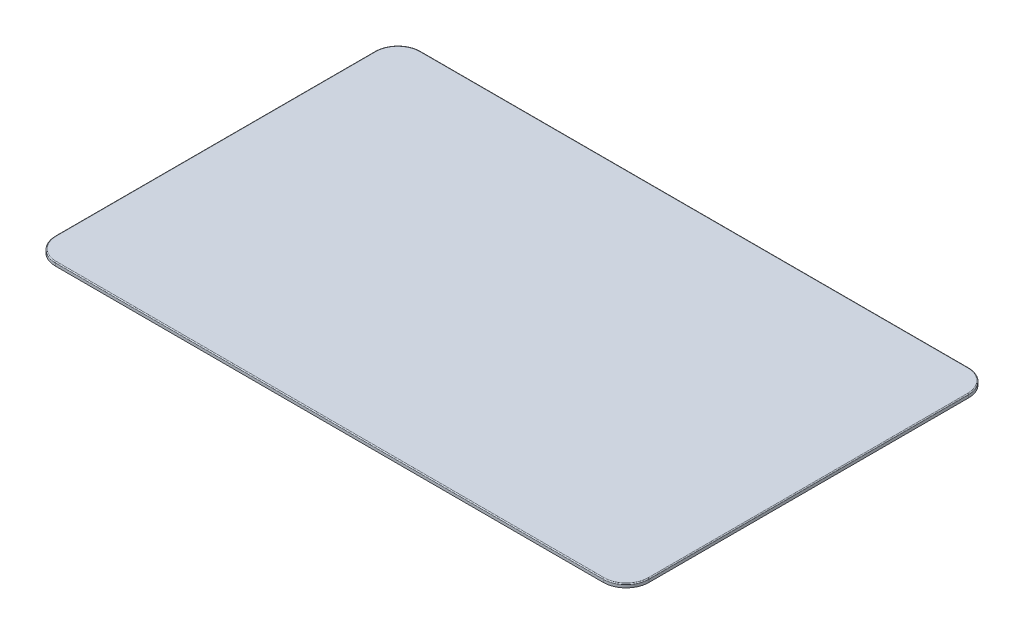
SolidWorks part; units mm, degrees
ref_plane "Спереди" through (0, 0, 0) normal (0, 0, 1) x (1, 0, 0)
ref_plane "Сверху" through (0, 0, 0) normal (0, 1, 0) x (1, 0, 0)
ref_plane "Справа" through (0, 0, 0) normal (1, 0, 0) x (0, 0, -1)
sketch "Эскиз1" plane through (0, 0, 0) normal (0, 1, 0) x (1, 0, 0)
  line L1 (-600, -400) -> (600, -400)
  line L2 (-650, -350) -> (-650, 350)
  line L3 (-600, 400) -> (600, 400)
  line L4 (650, -350) -> (650, 350)
  line L5 (-650, -400) -> (650, 400) construction
  line L6 (-650, 400) -> (650, -400) construction
  arc A0 (-600, 400) -> (-650, 350) centre (-600, 350) ccw
  arc A1 (600, 400) -> (650, 350) centre (600, 350) cw
  arc A2 (650, -350) -> (600, -400) centre (600, -350) cw
  arc A3 (-600, -400) -> (-650, -350) centre (-600, -350) cw
  point P0 (0, 0)
  dimension "D1" = 50
  dimension "D4" = 50
  dimension "D2" = 1300
  dimension "D3" = 800
extrude "Бобышка-Вытянуть1" add sketch "Эскиз1" along normal blind 8
fillet "Скругление1" radius 2 8 edges at (-635.3553, 8, -385.3553) (0, 8, -400) (635.3553, 8, -385.3553) (650, 8, 0) (635.3553, 8, 385.3553) (0, 8, 400) (-635.3553, 8, 385.3553) (-650, 8, 0)
sketch "Эскиз2" plane through (0, 0, 0) normal (0, -1, 0) x (1, 0, 0)
  line L0 (0, 398) -> (0, 115.0711) construction
  line L1 (-498, -35) -> (-405.9312, -35) construction
  line L2 (-494.82, 35) -> (-402.7512, 35) construction
  line L3 (-498, -100.1909) -> (-498, 80.8489) construction
  line L4 (-505.5, -118.7139) -> (-423, -118.7139)
  line L5 (-480.5, -93.7139) -> (-448, -93.7139)
  line L6 (-418, 113.7139) -> (-418, 19.5)
  line L7 (250, 398) -> (250, -398) construction
  line L8 (-250, 398) -> (-250, -398) construction
  line L9 (-648, 0) -> (648, 0) construction
  line L10 (302.5206, -212.9276) -> (307.7592, -212.906)
  line L12 (259.7408, -280.6043) -> (259.7408, -218.094)
  line L13 (262.2408, -283.1043) -> (308.0492, -283.1043)
  line L14 (265.5, -179.2861) -> (207.5, -179.2861)
  line L15 (-505.5, 118.7139) -> (-423, 118.7139)
  line L16 (-443, 88.7139) -> (-443, -88.7139)
  line L17 (-480.5, 93.7139) -> (-448, 93.7139)
  line L18 (-485.5, 84.9278) -> (-485.5, 88.7139)
  line L19 (-510.5, 85.0723) -> (-510.5, 113.7139)
  line L20 (-523.5388, 12.3957) -> (-523.2695, 77.6043)
  line L21 (418, -14.5) -> (302.5, -14.5)
  line L22 (418, 14.5) -> (302.5, 14.5)
  line L23 (418, -14.5) -> (418, -113.7139)
  line L24 (265.5, 174.2861) -> (207.5, 174.2861)
  line L25 (-515.5206, -80.0724) -> (-520.7592, -80.094)
  line L26 (267.5, 199.2861) -> (232.5, 199.2861)
  line L27 (270.5, -174.2861) -> (270.5, 169.2861)
  line L28 (197.4794, 212.9276) -> (192.2408, 212.906)
  line L29 (240.2592, 280.6043) -> (240.2592, 215.6043)
  line L30 (272.5, 208.0722) -> (272.5, 204.2861)
  line L31 (237.7592, 283.1043) -> (191.9508, 283.1043)
  line L32 (237.7592, 213.094) -> (232.4794, 213.0722)
  line L33 (310.5388, -280.6043) -> (310.2695, -215.3957)
  line L34 (-472.7408, -12.3957) -> (-472.7408, -77.3957)
  line L35 (297.5, -207.9277) -> (297.5, -19.5)
  line L36 (202.5, -207.9277) -> (202.5, -184.2861)
  line L37 (-475.2408, 79.906) -> (-480.5206, 79.9278)
  line L38 (-302.5206, 212.9276) -> (-307.7592, 212.906)
  line L39 (-265.5, 179.2861) -> (-207.5, 179.2861)
  line L40 (-259.7408, 280.6043) -> (-259.7408, 218.1043)
  line L41 (189.4612, -280.6043) -> (189.7305, -215.3957)
  line L42 (-262.2408, 283.1043) -> (-308.0492, 283.1043)
  line L43 (-254.7408, 213.1043) -> (-245.2592, 213.1043)
  line L44 (237.7592, -283.1043) -> (191.9508, -283.1043)
  line L46 (240.2592, -280.6043) -> (240.2592, -218.094)
  line L47 (197.4794, -212.9276) -> (192.2408, -212.906)
  line L50 (-310.5388, 280.6043) -> (-310.2695, 215.3957)
  line L51 (-297.5, 207.9277) -> (-297.5, 14.5)
  line L52 (-202.5, 207.9277) -> (-202.5, 184.2861)
  line L53 (-189.4612, 280.6043) -> (-189.7305, 215.3957)
  line L54 (-265.5, -174.2861) -> (-207.5, -174.2861)
  line L55 (-267.5, -199.2861) -> (-232.5, -199.2861)
  line L56 (-475.2408, -9.8957) -> (-521.0492, -9.8957)
  line L57 (-475.2408, -79.906) -> (-480.5206, -79.9278)
  line L58 (-475.2408, 9.8957) -> (-521.0492, 9.8957)
  line L59 (-523.5388, -12.3957) -> (-523.2695, -77.6043)
  line L60 (-510.5, -85.0723) -> (-510.5, -113.7139)
  line L61 (-472.7408, 12.3957) -> (-472.7408, 77.3957)
  line L62 (-515.5206, 80.0724) -> (-520.7592, 80.094)
  line L63 (-485.5, -84.9278) -> (-485.5, -88.7139)
  line L65 (-197.4794, -212.9276) -> (-192.2408, -212.906)
  line L66 (-240.2592, -280.6043) -> (-240.2592, -215.6043)
  line L67 (-272.5, -208.0722) -> (-272.5, -204.2861)
  line L68 (-237.7592, -283.1043) -> (-191.9508, -283.1043)
  line L69 (-237.7592, -213.094) -> (-232.4794, -213.0722)
  line L70 (485.5, -84.9278) -> (485.5, -88.7139)
  line L71 (-189.4612, -280.6043) -> (-189.7305, -215.3957)
  line L72 (-202.5, -207.9277) -> (-202.5, -179.2861)
  line L73 (-297.5, -207.9277) -> (-297.5, -14.5)
  line L74 (515.5206, 80.0724) -> (520.7592, 80.094)
  line L75 (472.7408, 12.3957) -> (472.7408, 77.3957)
  line L76 (510.5, -85.0723) -> (510.5, -113.7139)
  line L77 (523.5388, -12.3957) -> (523.2695, -77.6043)
  line L78 (475.2408, 9.8957) -> (521.0492, 9.8957)
  line L79 (475.2408, -79.906) -> (480.5206, -79.9278)
  line L80 (475.2408, -9.8957) -> (521.0492, -9.8957)
  line L81 (-102.1767, 35.0711) -> (-96.9381, 35.0927)
  line L82 (-142.4565, 34.9047) -> (-137.1767, 34.9265)
  line L83 (-94.1585, -32.6057) -> (-94.4278, 32.603)
  line L84 (-144.9565, -32.6056) -> (-144.9565, 32.3944)
  line L85 (-142.4565, -35.1056) -> (-96.6482, -35.1056)
  line L86 (-42.1767, 35.0711) -> (-36.9381, 35.0927)
  line L87 (-82.4565, 34.9047) -> (-77.1767, 34.9265)
  line L88 (-34.1585, -32.6057) -> (-34.4278, 32.603)
  line L89 (-84.9565, -32.6056) -> (-84.9565, 32.3944)
  line L90 (-82.4565, -35.1056) -> (-36.6482, -35.1056)
  line L91 (17.8233, 35.0711) -> (23.0619, 35.0927)
  line L92 (-22.4565, 34.9047) -> (-17.1767, 34.9265)
  line L93 (25.8415, -32.6057) -> (25.5722, 32.603)
  line L94 (-24.9565, -32.6056) -> (-24.9565, 32.3944)
  line L95 (-22.4565, -35.1056) -> (23.3518, -35.1056)
  line L96 (77.8233, 35.0711) -> (83.0619, 35.0927)
  line L97 (37.5435, 34.9047) -> (42.8233, 34.9265)
  line L98 (85.8415, -32.6057) -> (85.5722, 32.603)
  line L99 (35.0435, -32.6056) -> (35.0435, 32.3944)
  line L100 (37.5435, -35.1056) -> (83.3518, -35.1056)
  line L101 (137.9695, 35.0717) -> (143.0619, 35.0927)
  line L102 (97.5435, 34.9047) -> (102.0709, 34.9234)
  line L103 (145.8415, -32.6057) -> (145.5722, 32.603)
  line L104 (95.0435, -32.6056) -> (95.0435, 32.3944)
  line L105 (97.5435, -35.1056) -> (143.3518, -35.1056)
  line L106 (-132.1973, 39.9265) -> (-132.1973, 110.0711)
  line L107 (-107.1973, 40.071) -> (-107.1973, 85.0711)
  line L108 (0, 0) -> (0, -400) construction
  line L109 (67.8027, 80.0711) -> (17.8027, 80.0711)
  line L110 (107.1973, 40.071) -> (107.1973, 85.0711)
  line L112 (-310.5388, -280.6043) -> (-310.2695, -215.3957)
  line L114 (-237.7592, 283.1043) -> (-191.9508, 283.1043)
  line L116 (-240.2592, 280.6043) -> (-240.2592, 218.1043)
  line L117 (-197.4794, 212.9276) -> (-192.2408, 212.906)
  line L118 (-270.5, 174.2861) -> (-270.5, -169.2861)
  line L122 (-418, -19.5) -> (-418, -113.7139)
  line L123 (189.4612, 280.6043) -> (189.7305, 215.3957)
  line L124 (202.5, 207.9277) -> (202.5, 179.2861)
  line L125 (297.5, 207.9277) -> (297.5, 19.5)
  line L126 (310.5388, 280.6043) -> (310.2695, 215.3957)
  line L127 (262.2408, 213.094) -> (267.5206, 213.0722)
  line L128 (262.2408, 283.1043) -> (308.0492, 283.1043)
  line L129 (259.7408, 280.6043) -> (259.7408, 215.6043)
  line L130 (227.5, 208.0722) -> (227.5, 204.2861)
  line L131 (302.5206, 212.9276) -> (307.7592, 212.906)
  line L132 (498, -100.1909) -> (498, 80.8489) construction
  line L133 (475.2408, 79.906) -> (480.5206, 79.9278)
  line L134 (472.7408, -12.3957) -> (472.7408, -77.3957)
  line L135 (515.5206, -80.0724) -> (520.7592, -80.094)
  line L136 (523.5388, 12.3957) -> (523.2695, 77.6043)
  line L137 (-413, 14.5) -> (-297.5, 14.5)
  line L138 (-413, -14.5) -> (-297.5, -14.5)
  line L139 (-262.2408, -213.094) -> (-267.5206, -213.0722)
  line L140 (510.5, 85.0723) -> (510.5, 113.7139)
  line L141 (485.5, 84.9278) -> (485.5, 88.7139)
  line L142 (-262.2408, -283.1043) -> (-308.0492, -283.1043)
  line L143 (494.82, 35) -> (402.7512, 35) construction
  line L144 (498, -35) -> (405.9312, -35) construction
  line L145 (480.5, 93.7139) -> (448, 93.7139)
  line L146 (443, 88.7139) -> (443, -88.7139)
  line L147 (505.5, 118.7139) -> (423, 118.7139)
  line L148 (418, 113.7139) -> (418, 14.5)
  line L149 (480.5, -93.7139) -> (448, -93.7139)
  line L150 (-259.7408, -280.6043) -> (-259.7408, -215.6043)
  line L151 (505.5, -118.7139) -> (423, -118.7139)
  line L152 (-227.5, -208.0722) -> (-227.5, -204.2861)
  line L153 (-302.5206, -212.9276) -> (-307.7592, -212.906)
  line L154 (72.8027, 40.071) -> (72.8027, 50.0711)
  line L155 (47.8027, 39.9265) -> (47.8027, 50.0711)
  line L156 (12.8027, 40.071) -> (12.8027, 50.0711)
  line L157 (-12.1973, 39.9265) -> (-12.1973, 50.0711)
  line L158 (-47.1973, 40.071) -> (-47.1973, 50.0711)
  line L159 (-72.1973, 39.9265) -> (-72.1973, 50.0711)
  line L160 (254.7408, -213.094) -> (245.2592, -213.094)
  line L161 (42.8027, 55.0711) -> (17.8027, 55.0711)
  line L162 (-17.1973, 55.0711) -> (-42.1973, 55.0711)
  line L163 (102.1973, 90.0711) -> (17.1973, 90.0711)
  line L164 (72.8027, 50.0711) -> (72.8027, 75.0711)
  line L165 (-72.1973, 50.0711) -> (-72.1973, 75.0711)
  line L166 (127.8027, 115.0711) -> (-127.1973, 115.0711)
  line L167 (-102.1973, 90.0711) -> (-17.1973, 90.0711)
  line L170 (-17.1973, 80.0711) -> (-67.1973, 80.0711)
  line L171 (132.8027, 40.071) -> (132.8027, 110.0711)
  arc A0 (240.2592, -218.094) -> (245.2592, -213.094) centre (245.2592, -218.094) cw
  arc A1 (297.5, -207.9277) -> (302.5206, -212.9276) centre (302.5, -207.9277) ccw
  arc A2 (310.2695, -215.3957) -> (307.7592, -212.906) centre (310.2592, -212.8957) ccw
  arc A3 (267.5, 199.2861) -> (272.5, 204.2861) centre (267.5, 204.2861) ccw
  arc A4 (227.5, 204.2861) -> (232.5, 199.2861) centre (232.5, 204.2861) ccw
  arc A5 (202.5, -184.2861) -> (207.5, -179.2861) centre (207.5, -184.2861) cw
  arc A6 (308.0492, -283.1043) -> (310.5388, -280.6043) centre (310.5492, -283.1043) ccw
  arc A7 (259.7408, -280.6043) -> (262.2408, -283.1043) centre (259.7408, -283.1043) ccw
  arc A8 (240.2592, -280.6043) -> (237.7592, -283.1043) centre (240.2592, -283.1043) cw
  arc A9 (191.9508, -283.1043) -> (189.4612, -280.6043) centre (189.4508, -283.1043) cw
  arc A10 (270.5, 169.2861) -> (265.5, 174.2861) centre (265.5, 169.2861) ccw
  arc A11 (510.5, 113.7139) -> (505.5, 118.7139) centre (505.5, 113.7139) ccw
  arc A12 (265.5, -179.2861) -> (270.5, -174.2861) centre (265.5, -174.2861) ccw
  arc A13 (189.7305, -215.3957) -> (192.2408, -212.906) centre (189.7408, -212.8957) cw
  arc A14 (202.5, -207.9277) -> (197.4794, -212.9276) centre (197.5, -207.9277) cw
  arc A15 (254.7408, -213.094) -> (259.7408, -218.094) centre (254.7408, -218.094) cw
  arc A16 (-240.2592, 218.1043) -> (-245.2592, 213.1043) centre (-245.2592, 218.1043) cw
  arc A17 (505.5, -118.7139) -> (510.5, -113.7139) centre (505.5, -113.7139) ccw
  arc A18 (-254.7408, 213.1043) -> (-259.7408, 218.1043) centre (-254.7408, 218.1043) cw
  arc A19 (-202.5, 184.2861) -> (-207.5, 179.2861) centre (-207.5, 184.2861) cw
  arc A20 (232.4794, 213.0722) -> (227.5, 208.0722) centre (232.5, 208.0722) ccw
  arc A21 (202.5, 207.9277) -> (197.4794, 212.9276) centre (197.5, 207.9277) ccw
  arc A22 (189.7305, 215.3957) -> (192.2408, 212.906) centre (189.7408, 212.8957) ccw
  arc A23 (237.7592, 213.094) -> (240.2592, 215.6043) centre (240.2592, 213.1043) ccw
  arc A24 (191.9508, 283.1043) -> (189.4612, 280.6043) centre (189.4508, 283.1043) ccw
  arc A25 (240.2592, 280.6043) -> (237.7592, 283.1043) centre (240.2592, 283.1043) ccw
  arc A26 (259.7408, 280.6043) -> (262.2408, 283.1043) centre (259.7408, 283.1043) cw
  arc A27 (308.0492, 283.1043) -> (310.5388, 280.6043) centre (310.5492, 283.1043) cw
  arc A28 (262.2408, 213.094) -> (259.7408, 215.6043) centre (259.7408, 213.1043) cw
  arc A29 (310.2695, 215.3957) -> (307.7592, 212.906) centre (310.2592, 212.8957) cw
  arc A30 (297.5, 207.9277) -> (302.5206, 212.9276) centre (302.5, 207.9277) cw
  arc A31 (267.5206, 213.0722) -> (272.5, 208.0722) centre (267.5, 208.0722) cw
  arc A32 (202.5, 179.2861) -> (207.5, 174.2861) centre (207.5, 179.2861) ccw
  arc A33 (-270.5, -169.2861) -> (-265.5, -174.2861) centre (-265.5, -169.2861) ccw
  arc A34 (485.5, 88.7139) -> (480.5, 93.7139) centre (480.5, 88.7139) ccw
  arc A35 (-443, -88.7139) -> (-448, -93.7139) centre (-448, -88.7139) cw
  arc A36 (480.5206, 79.9278) -> (485.5, 84.9278) centre (480.5, 84.9278) ccw
  arc A37 (510.5, 85.0723) -> (515.5206, 80.0724) centre (515.5, 85.0723) ccw
  arc A38 (472.7408, -12.3957) -> (475.2408, -9.8957) centre (472.7408, -9.8957) cw
  arc A39 (521.0492, -9.8957) -> (523.5388, -12.3957) centre (523.5492, -9.8957) cw
  arc A40 (475.2408, -79.906) -> (472.7408, -77.3957) centre (472.7408, -79.8957) cw
  arc A41 (523.2695, -77.6043) -> (520.7592, -80.094) centre (523.2592, -80.1043) cw
  arc A42 (510.5, -85.0723) -> (515.5206, -80.0724) centre (515.5, -85.0723) cw
  arc A43 (480.5206, -79.9278) -> (485.5, -84.9278) centre (480.5, -84.9278) cw
  arc A44 (523.2695, 77.6043) -> (520.7592, 80.094) centre (523.2592, 80.1043) ccw
  arc A45 (-418, -113.7139) -> (-423, -118.7139) centre (-423, -113.7139) cw
  arc A46 (485.5, -88.7139) -> (480.5, -93.7139) centre (480.5, -88.7139) cw
  arc A47 (475.2408, 79.906) -> (472.7408, 77.3957) centre (472.7408, 79.8957) ccw
  arc A48 (521.0492, 9.8957) -> (523.5388, 12.3957) centre (523.5492, 9.8957) ccw
  arc A49 (472.7408, 12.3957) -> (475.2408, 9.8957) centre (472.7408, 9.8957) ccw
  arc A50 (-443, 88.7139) -> (-448, 93.7139) centre (-448, 88.7139) ccw
  arc A51 (-418, 113.7139) -> (-423, 118.7139) centre (-423, 113.7139) ccw
  arc A52 (418, 113.7139) -> (423, 118.7139) centre (423, 113.7139) cw
  arc A53 (443, 88.7139) -> (448, 93.7139) centre (448, 88.7139) cw
  arc A54 (418, -113.7139) -> (423, -118.7139) centre (423, -113.7139) ccw
  arc A55 (443, -88.7139) -> (448, -93.7139) centre (448, -88.7139) ccw
  arc A56 (-472.7408, 12.3957) -> (-475.2408, 9.8957) centre (-472.7408, 9.8957) cw
  arc A57 (-521.0492, 9.8957) -> (-523.5388, 12.3957) centre (-523.5492, 9.8957) cw
  arc A58 (-475.2408, 79.906) -> (-472.7408, 77.3957) centre (-472.7408, 79.8957) cw
  arc A59 (-485.5, -88.7139) -> (-480.5, -93.7139) centre (-480.5, -88.7139) ccw
  arc A60 (-523.2695, 77.6043) -> (-520.7592, 80.094) centre (-523.2592, 80.1043) cw
  arc A61 (-480.5206, -79.9278) -> (-485.5, -84.9278) centre (-480.5, -84.9278) ccw
  arc A62 (-510.5, -85.0723) -> (-515.5206, -80.0724) centre (-515.5, -85.0723) ccw
  arc A63 (-523.2695, -77.6043) -> (-520.7592, -80.094) centre (-523.2592, -80.1043) ccw
  arc A64 (-475.2408, -79.906) -> (-472.7408, -77.3957) centre (-472.7408, -79.8957) ccw
  arc A65 (-521.0492, -9.8957) -> (-523.5388, -12.3957) centre (-523.5492, -9.8957) ccw
  arc A66 (-472.7408, -12.3957) -> (-475.2408, -9.8957) centre (-472.7408, -9.8957) ccw
  arc A67 (-510.5, 85.0723) -> (-515.5206, 80.0724) centre (-515.5, 85.0723) cw
  arc A68 (-480.5206, 79.9278) -> (-485.5, 84.9278) centre (-480.5, 84.9278) cw
  arc A69 (-485.5, 88.7139) -> (-480.5, 93.7139) centre (-480.5, 88.7139) cw
  arc A70 (-202.5, -179.2861) -> (-207.5, -174.2861) centre (-207.5, -179.2861) ccw
  arc A71 (-270.5, 174.2861) -> (-265.5, 179.2861) centre (-265.5, 174.2861) cw
  arc A72 (297.5, 19.5) -> (302.5, 14.5) centre (302.5, 19.5) ccw
  arc A73 (-297.5, 207.9277) -> (-302.5206, 212.9276) centre (-302.5, 207.9277) ccw
  arc A74 (-310.2695, 215.3957) -> (-307.7592, 212.906) centre (-310.2592, 212.8957) ccw
  arc A75 (297.5, -19.5) -> (302.5, -14.5) centre (302.5, -19.5) cw
  arc A76 (-308.0492, 283.1043) -> (-310.5388, 280.6043) centre (-310.5492, 283.1043) ccw
  arc A77 (-259.7408, 280.6043) -> (-262.2408, 283.1043) centre (-259.7408, 283.1043) ccw
  arc A78 (-240.2592, 280.6043) -> (-237.7592, 283.1043) centre (-240.2592, 283.1043) cw
  arc A79 (-191.9508, 283.1043) -> (-189.4612, 280.6043) centre (-189.4508, 283.1043) cw
  arc A80 (-418, 19.5) -> (-413, 14.5) centre (-413, 19.5) ccw
  arc A81 (-189.7305, 215.3957) -> (-192.2408, 212.906) centre (-189.7408, 212.8957) cw
  arc A82 (-202.5, 207.9277) -> (-197.4794, 212.9276) centre (-197.5, 207.9277) cw
  arc A83 (-418, -19.5) -> (-413, -14.5) centre (-413, -19.5) cw
  arc A84 (-267.5, -199.2861) -> (-272.5, -204.2861) centre (-267.5, -204.2861) ccw
  arc A85 (-227.5, -204.2861) -> (-232.5, -199.2861) centre (-232.5, -204.2861) ccw
  arc A86 (-505.5, -118.7139) -> (-510.5, -113.7139) centre (-505.5, -113.7139) cw
  arc A88 (-232.4794, -213.0722) -> (-227.5, -208.0722) centre (-232.5, -208.0722) ccw
  arc A89 (-202.5, -207.9277) -> (-197.4794, -212.9276) centre (-197.5, -207.9277) ccw
  arc A90 (-189.7305, -215.3957) -> (-192.2408, -212.906) centre (-189.7408, -212.8957) ccw
  arc A92 (-510.5, 113.7139) -> (-505.5, 118.7139) centre (-505.5, 113.7139) cw
  arc A93 (-237.7592, -213.094) -> (-240.2592, -215.6043) centre (-240.2592, -213.1043) ccw
  arc A94 (-191.9508, -283.1043) -> (-189.4612, -280.6043) centre (-189.4508, -283.1043) ccw
  arc A95 (-240.2592, -280.6043) -> (-237.7592, -283.1043) centre (-240.2592, -283.1043) ccw
  arc A96 (-259.7408, -280.6043) -> (-262.2408, -283.1043) centre (-259.7408, -283.1043) cw
  arc A97 (-308.0492, -283.1043) -> (-310.5388, -280.6043) centre (-310.5492, -283.1043) cw
  arc A98 (-262.2408, -213.094) -> (-259.7408, -215.6043) centre (-259.7408, -213.1043) cw
  arc A101 (-310.2695, -215.3957) -> (-307.7592, -212.906) centre (-310.2592, -212.8957) cw
  arc A102 (-297.5, -207.9277) -> (-302.5206, -212.9276) centre (-302.5, -207.9277) cw
  arc A103 (-267.5206, -213.0722) -> (-272.5, -208.0722) centre (-267.5, -208.0722) cw
  arc A104 (-137.1767, 34.9265) -> (-132.1973, 39.9265) centre (-137.1973, 39.9265) ccw
  arc A105 (-144.9565, -32.6056) -> (-142.4565, -35.1056) centre (-144.9565, -35.1056) ccw
  arc A106 (-107.1973, 40.071) -> (-102.1767, 35.0711) centre (-102.1973, 40.071) ccw
  arc A107 (-94.4278, 32.603) -> (-96.9381, 35.0927) centre (-94.4381, 35.103) ccw
  arc A108 (-142.4565, 34.9047) -> (-144.9565, 32.3944) centre (-144.9565, 34.8944) ccw
  arc A109 (-96.6482, -35.1056) -> (-94.1585, -32.6057) centre (-94.1482, -35.1056) ccw
  arc A110 (-77.1767, 34.9265) -> (-72.1973, 39.9265) centre (-77.1973, 39.9265) ccw
  arc A111 (-84.9565, -32.6056) -> (-82.4565, -35.1056) centre (-84.9565, -35.1056) ccw
  arc A112 (-47.1973, 40.071) -> (-42.1767, 35.0711) centre (-42.1973, 40.071) ccw
  arc A113 (-34.4278, 32.603) -> (-36.9381, 35.0927) centre (-34.4381, 35.103) ccw
  arc A114 (-82.4565, 34.9047) -> (-84.9565, 32.3944) centre (-84.9565, 34.8944) ccw
  arc A115 (-36.6482, -35.1056) -> (-34.1585, -32.6057) centre (-34.1482, -35.1056) ccw
  arc A116 (-17.1767, 34.9265) -> (-12.1973, 39.9265) centre (-17.1973, 39.9265) ccw
  arc A117 (-24.9565, -32.6056) -> (-22.4565, -35.1056) centre (-24.9565, -35.1056) ccw
  arc A118 (12.8027, 40.071) -> (17.8233, 35.0711) centre (17.8027, 40.071) ccw
  arc A119 (25.5722, 32.603) -> (23.0619, 35.0927) centre (25.5619, 35.103) ccw
  arc A120 (-22.4565, 34.9047) -> (-24.9565, 32.3944) centre (-24.9565, 34.8944) ccw
  arc A121 (23.3518, -35.1056) -> (25.8415, -32.6057) centre (25.8518, -35.1056) ccw
  arc A122 (42.8233, 34.9265) -> (47.8027, 39.9265) centre (42.8027, 39.9265) ccw
  arc A123 (35.0435, -32.6056) -> (37.5435, -35.1056) centre (35.0435, -35.1056) ccw
  arc A124 (72.8027, 40.071) -> (77.8233, 35.0711) centre (77.8027, 40.071) ccw
  arc A125 (85.5722, 32.603) -> (83.0619, 35.0927) centre (85.5619, 35.103) ccw
  arc A126 (37.5435, 34.9047) -> (35.0435, 32.3944) centre (35.0435, 34.8944) ccw
  arc A127 (83.3518, -35.1056) -> (85.8415, -32.6057) centre (85.8518, -35.1056) ccw
  arc A128 (102.0709, 34.9234) -> (107.1973, 40.071) centre (102.0497, 40.071) ccw
  arc A129 (95.0435, -32.6056) -> (97.5435, -35.1056) centre (95.0435, -35.1056) ccw
  arc A130 (132.8027, 40.071) -> (137.9695, 35.0717) centre (137.9482, 40.2193) ccw
  arc A131 (145.5722, 32.603) -> (143.0619, 35.0927) centre (145.5619, 35.103) ccw
  arc A132 (97.5435, 34.9047) -> (95.0435, 32.3944) centre (95.0435, 34.8944) ccw
  arc A133 (143.3518, -35.1056) -> (145.8415, -32.6057) centre (145.8518, -35.1056) ccw
  arc A134 (17.1973, 90.0711) -> (17.8027, 80.0711) centre (17.1973, 85.0527) ccw
  arc A135 (-17.1973, 80.0711) -> (-17.1973, 90.0711) centre (-17.1973, 85.0711) ccw
  arc A136 (-42.1973, 55.0711) -> (-47.1973, 50.0711) centre (-42.1973, 50.0711) ccw
  arc A137 (-17.1973, 55.0711) -> (-12.1973, 50.0711) centre (-17.1973, 50.0711) cw
  arc A138 (17.8027, 55.0711) -> (12.8027, 50.0711) centre (17.8027, 50.0711) ccw
  arc A139 (47.8027, 50.0711) -> (42.8027, 55.0711) centre (42.8027, 50.0711) ccw
  arc A140 (-72.1973, 75.0711) -> (-67.1973, 80.0711) centre (-67.1973, 75.0711) cw
  arc A141 (107.1973, 85.0711) -> (102.1973, 90.0711) centre (102.1973, 85.0711) ccw
  arc A142 (127.8027, 115.0711) -> (132.8027, 110.0711) centre (127.8027, 110.0711) cw
  arc A143 (-107.1973, 85.0711) -> (-102.1973, 90.0711) centre (-102.1973, 85.0711) cw
  arc A144 (-127.1973, 115.0711) -> (-132.1973, 110.0711) centre (-127.1973, 110.0711) ccw
  arc A145 (67.8027, 80.0711) -> (72.8027, 75.0711) centre (67.8027, 75.0711) cw
  point P24 (285, -248)
  point P39 (285, -213)
  point P75 (202.5, -179.2861)
  point P79 (0, 0)
  point P84 (60, 0)
  point P85 (-119.6973, -0.0013)
  point P86 (-119.6973, 34.9987)
  point P89 (120, 0)
  point P94 (-60, 0)
  point P99 (-120, 0)
  point P139 (215, -213)
  point P140 (215, -248)
  point P141 (250, -186.7861)
  point P142 (250, -186.7861)
  point P144 (-240.2592, 213.1043)
  point P148 (-259.7408, 213.1043)
  point P199 (250, 186.7861)
  point P200 (215, 248)
  point P201 (215, 213)
  point P202 (285, 213)
  point P203 (285, 248)
  point P241 (498, -80)
  point P242 (498, -45)
  point P243 (463, -106.2139)
  point P244 (463, -106.2139)
  point P267 (-202.5, 179.2861)
  point P268 (463, 106.2139)
  point P269 (498, 45)
  point P270 (498, 80)
  point P384 (-498, 80)
  point P385 (-498, 45)
  point P388 (-463, 106.2139)
  point P389 (-463, -106.2139)
  point P390 (-498, -45)
  point P391 (-498, -80)
  point P392 (-285, 248)
  point P393 (-285, 213)
  point P394 (-215, 213)
  point P395 (-215, 248)
  point P396 (-250, 186.7861)
  point P397 (-250, -186.7861)
  point P398 (-215, -248)
  point P399 (-215, -213)
  point P400 (-285, -213)
  point P401 (-285, -248)
  point P406 (-59.6973, -0.0013)
  point P407 (-59.6973, 34.9987)
  point P426 (0.3027, -0.0013)
  point P427 (0.3027, 34.9987)
  point P446 (60.3027, -0.0013)
  point P447 (60.3027, 34.9987)
  point P466 (120.3027, -0.0013)
  point P467 (120.3027, 34.9987)
  point P494 (-107.1973, 55.0711)
  point P497 (-72.1973, 55.0711)
  point P500 (-47.1973, 55.0711)
  point P503 (-12.1973, 55.0711)
  point P506 (12.8027, 55.0711)
  point P509 (47.8027, 55.0711)
  point P518 (0.3027, 80.0711)
  dimension "D2" = 5
  dimension "D3" = 5
  dimension "D4" = 5
  dimension "D6" = 5
  dimension "D7" = 5
  dimension "D8" = 5
  dimension "D9" = 5
  dimension "D10" = 5.1477
  dimension "D11" = 5
  dimension "D12" = 5
  dimension "D13" = 5
  dimension "D14" = 5
  dimension "D15" = 5
  dimension "D16" = 5
  dimension "D17" = 5
  dimension "D18" = 5
  dimension "D19" = 5
  dimension "D20" = 5
  dimension "D5" = 5
extrude "Вырез-Вытянуть1" cut sketch "Эскиз2" against normal blind 6
